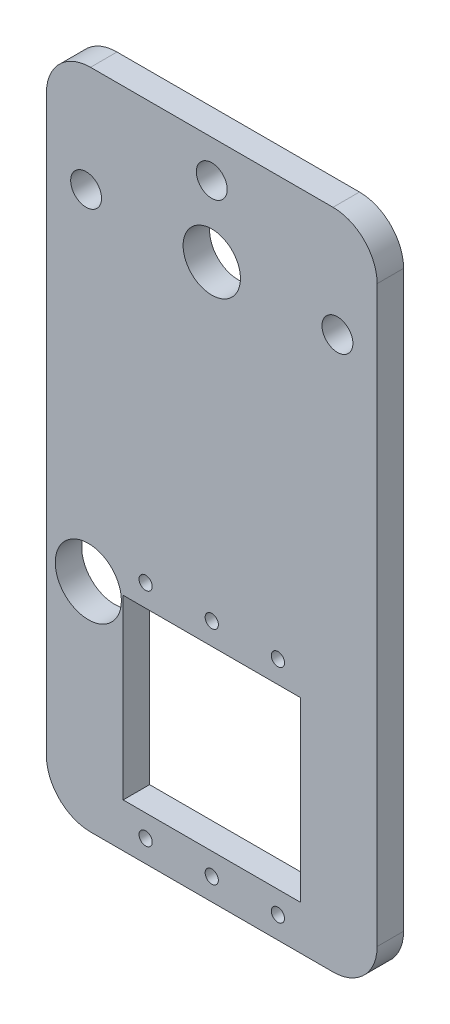
SolidWorks part; units mm, degrees
ref_plane "Alzado" through (0, 0, 0) normal (0, 0, 1) x (1, 0, 0)
ref_plane "Planta" through (0, 0, 0) normal (0, 1, 0) x (1, 0, 0)
ref_plane "Vista lateral" through (0, 0, 0) normal (1, 0, 0) x (0, 0, -1)
sketch "Croquis2" plane through (0, 0, 0) normal (0, 0, 1) x (1, 0, 0)
  line L0 (-28.5, 50.6) -> (28.5, 50.6) construction
  line L1 (-37.5, 75.1) -> (37.5, 75.1)
  line L2 (-37.5, 75.1) -> (-37.5, -75.1)
  line L3 (-37.5, -75.1) -> (37.5, -75.1)
  line L4 (37.5, 75.1) -> (37.5, -75.1)
  line L5 (-37.5, 75.1) -> (37.5, -75.1) construction
  line L6 (-37.5, -75.1) -> (37.5, 75.1) construction
  line L7 (0, 0) -> (0, 50.6) construction
  line L8 (0, 50.6) -> (0, 66.6) construction
  line L9 (0, 70.1) -> (0, 75.1) construction
  line L10 (0, 0) -> (0, -45) construction
  line L11 (-15, -70.1) -> (15, -70.1) construction
  line L12 (-20.1, -24.9) -> (20.1, -24.9)
  line L13 (-20.1, -24.9) -> (-20.1, -65.1)
  line L14 (-20.1, -65.1) -> (20.1, -65.1)
  line L15 (20.1, -24.9) -> (20.1, -65.1)
  line L16 (-20.1, -24.9) -> (20.1, -65.1) construction
  line L17 (-20.1, -65.1) -> (20.1, -24.9) construction
  line L18 (-15, -19.9) -> (15, -19.9) construction
  line L19 (-15, -19.9) -> (-15, -24.9) construction
  line L20 (-15, -70.1) -> (-15, -65.1) construction
  line L21 (20, -65.1) -> (-20, -65.1) construction
  line L22 (0, -45) -> (0, -70.1) construction
  circle A0 centre (-28.5, 50.6) radius 3.5
  circle A1 centre (28.5, 50.6) radius 3.5
  circle A2 centre (0, 66.6) radius 3.5
  circle A3 centre (0, -19.9) radius 1.5
  circle A4 centre (-15, -19.9) radius 1.5
  circle A5 centre (15, -19.9) radius 1.5
  circle A6 centre (-15, -70.1) radius 1.5
  circle A7 centre (0, -70.1) radius 1.5
  circle A8 centre (15, -70.1) radius 1.5
  circle A9 centre (0, 50.6) radius 6.5
  point P0 (0, 0)
  point P9 (0, 50.6)
  point P25 (0, -70.1)
  point P28 (0, -19.9)
  dimension "D1" = 7
  dimension "D10" = 3
  dimension "D12" = 13
  dimension "D2" = 57
  dimension "D3" = 16
  dimension "D4" = 5
  dimension "D5" = 100
  dimension "D6" = 75
  dimension "D7" = 40.2
  dimension "D8" = 10
  dimension "D9" = 5
  dimension "D11" = 30
extrude "Saliente-Extruir1" add sketch "Croquis2" against normal blind 6
sketch "Croquis4" plane through (0, 0, 0) normal (0, 0, 1) x (1, 0, 0)
  line L0 (-37.5, -75.1) -> (37.5, -75.1) construction
  line L1 (-37.5, 75.1) -> (37.5, 75.1)
  line L2 (-37.5, 75.1) -> (-37.5, -75.1)
  line L3 (-37.5, -75.1) -> (37.5, -75.1)
  line L4 (37.5, 75.1) -> (37.5, -75.1)
  line L5 (-37.5, 75.1) -> (37.5, -75.1) construction
  line L6 (-37.5, -75.1) -> (37.5, 75.1) construction
  point P0 (0, 0)
  dimension "D1" = 75
sketch "Croquis3" plane through (0, 0, 0) normal (0, 0, 1) x (1, 0, 0)
  line L0 (0, -45) -> (0, -24.9) construction
  line L1 (20.1, -24.9) -> (-20.1, -24.9) construction
  line L2 (0, -45) -> (-20.1, -45) construction
  line L3 (-20.1, -24.9) -> (-20.1, -65.1) construction
  line L4 (-35.5, 3.5608) -> (-35.5, -55.8746)
  line L6 (-37.5, 75.1) -> (-37.5, -75.1) construction
  circle A0 centre (0, -45) radius 21.25 construction
  circle A1 centre (0, -45) radius 26.25 construction
  circle A2 centre (-28, -26.1569) radius 7.5
  point P14 (-35.5, -26.1569)
  dimension "D1" = 42.5
  dimension "D2" = 5
  dimension "D3" = 15
  dimension "D4" = 2
extrude "Cortar-Extruir1" cut sketch "Croquis3" against normal blind 13 contours A2
fillet "Redondeo1" radius 10 4 edges at (-37.5, 75.1, -3) (37.5, 75.1, -3) (37.5, -75.1, -3) (-37.5, -75.1, -3)
